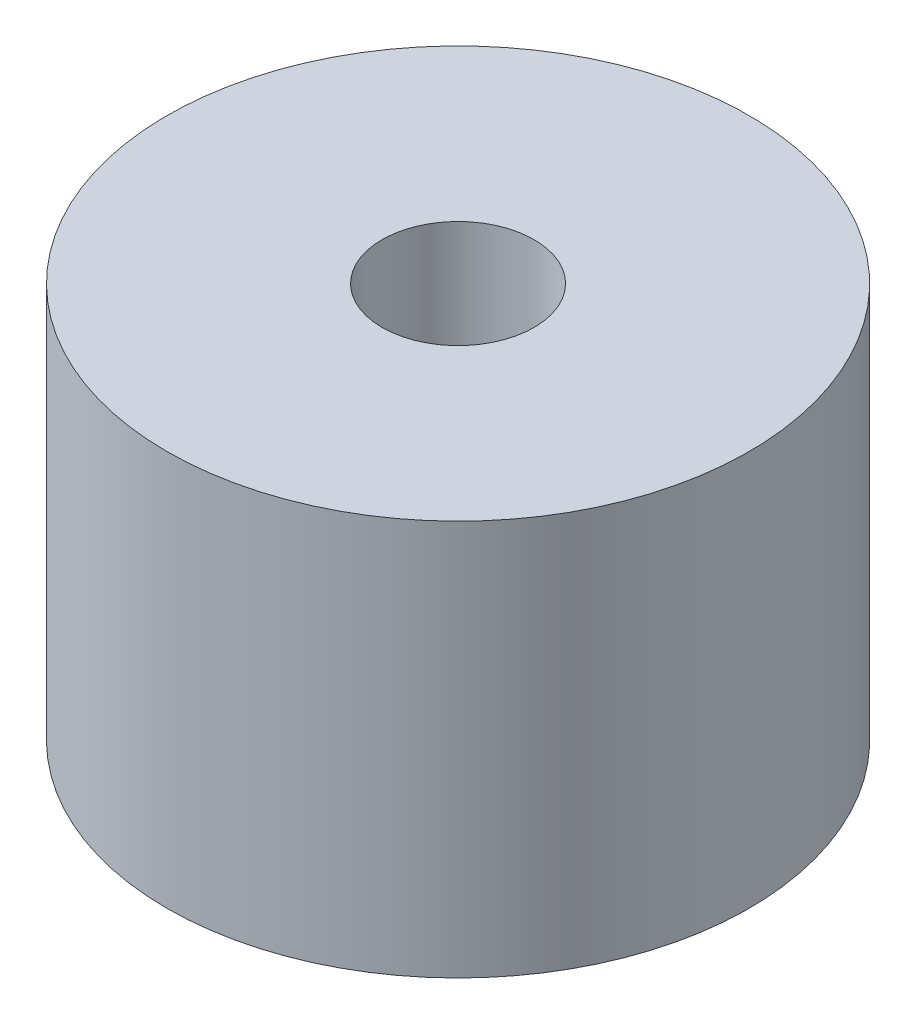
SolidWorks part; units mm, degrees
material "PTFE (general)"
ref_plane "Front Plane" through (0, 0, 0) normal (0, 0, 1) x (1, 0, 0)
ref_plane "Top Plane" through (0, 0, 0) normal (0, 1, 0) x (1, 0, 0)
ref_plane "Right Plane" through (0, 0, 0) normal (1, 0, 0) x (0, 0, -1)
sketch "Sketch1" plane through (0, 0, 0) normal (0, 1, 0) x (1, 0, 0)
  circle A0 centre (0, 0) radius 9.525
  dimension "D1" = 19.05
extrude "Boss-Extrude1" add sketch "Sketch1" along normal blind 12.9476
hole_wizard "#10 Clearance Hole1" positions "Sketch2" profile "Sketch3" hole size "#10" standard "ANSI Inch" end condition through all
sketch "Sketch2" plane through (0, 12.9476, 0) normal (0, 1, 0) x (1, 0, 0)
  point P0 (0, 0)
sketch "Sketch3" plane through (0, 12.9476, 0) normal (1, 0, 0) x (0, 0, 1)
  line L0 (0, 0) -> (0, 12.9476)
  line L1 (0, 12.9476) -> (2.4892, 12.9476)
  line L2 (2.4892, 12.9476) -> (2.4892, 0)
  line L5 (2.4892, 0) -> (0, 0)
  line L11 (0, -6.35) -> (0, 107.95) construction
  dimension "Thru Hole Dia." = 4.9784
  dimension "Thru Hole Depth" = 12.9476
